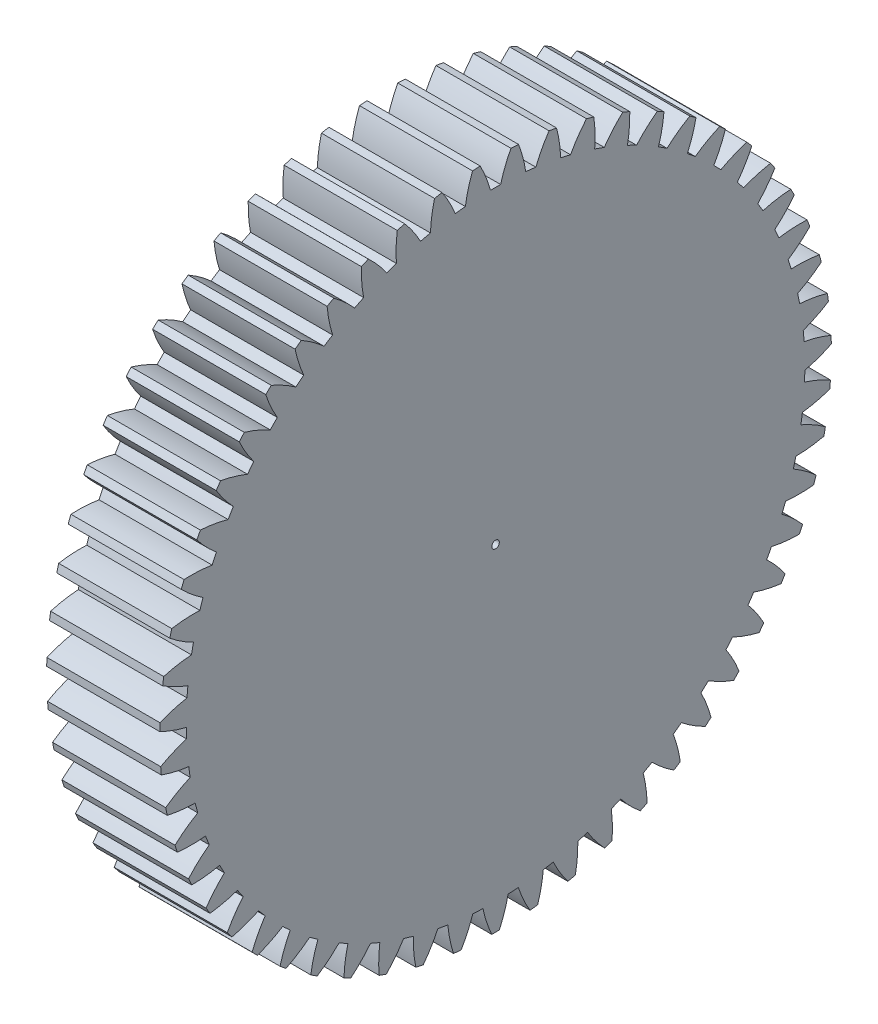
SolidWorks part; units mm, degrees
ref_plane "Plane1" through (0, 0, 0) normal (0, 0, 1) x (1, 0, 0)
ref_plane "Plane2" through (0, 0, 0) normal (0, 1, 0) x (1, 0, 0)
ref_plane "Plane3" through (0, 0, 0) normal (1, 0, 0) x (0, 0, -1)
other "Configuration Table"
sketch "HoldingSke" plane through (0, 0, 0) normal (0, 1, 0) x (1, 0, 0)
  line L0 (0, 0) -> (0.4589, -0.6553)
  line L1 (-15, 0) -> (100, 0) construction
  line L2 (0, 0) -> (-2.1039, 2.3779)
  line L3 (0, 0) -> (-11.863, 4.5341)
  line L4 (0, 0) -> (4.9534, 7.0742)
  line L5 (0, 0) -> (-46.8476, -17.4728)
  line L6 (0, 0) -> (-9.9476, -6.7116)
  line L7 (-2.1039, 2.3779) -> (8.6586, 51.2059)
  line L8 (-76.2, 54.61) -> (-76.1, 54.61)
  line L9 (-71.009, 38.7566) -> (-53.1078, 45.2721)
  line L10 (-76.2, 71.12) -> (104.1128, 71.12)
  line L11 (0, 0) -> (-12, 0)
  line L12 (-76.2, 101.6) -> (-76.155, 101.6)
  line L13 (24.9733, 27.94) -> (52.9518, 28.4284)
  line L14 (24.9733, 27.94) -> (24.9743, 27.94)
  line L15 (24.9733, 27.94) -> (100.4006, 29.5858)
  line L16 (-63.627, -1.25) -> (-12.827, -1.25)
  circle A0 centre (0, 0) radius 0.4
  circle A1 centre (0, 0) radius 32.8115
  circle A2 centre (0, 0) radius 37.5
  circle A3 centre (0, 0) radius 0.4
  dimension "MHD" = 65.623
  dimension "Hub_dia" = 75
  dimension "Bore" = 0.8
  dimension "MBD" = 0.8
  dimension "Num_teeth" = 55
  dimension "Pitch" = 0.8
  dimension "Overall_len" = 50
  dimension "Show_teeth" = 55
  dimension "Thickness" = 12
  dimension "OAL" = 50.0001
  dimension "T_dim" = 0.1
  dimension "Ap" = 20
  dimension "H" = 19.05
  dimension "Pitch_radius" = 180.3128
  dimension "Width" = 12
  dimension "Backlash" = 0.045
  dimension "Addendum_fac" = 1
  dimension "Dedendum_fac" = 1.25
  dimension "Clearance_fac" = 0.25
  dimension "Dedendum_add" = 0.001
  dimension "Module" = 1.25
sketch "BasProSke" plane through (0, 0, 0) normal (0, 1, 0) x (1, 0, 0)
  line L0 (-10, 0) -> (60, 0) construction
  line L1 (0, 0) -> (0, 35.625)
  line L2 (0, 0) -> (12, 0)
  line L3 (12, 0) -> (12, 35.625)
  line L4 (12, 35.625) -> (0, 35.625)
  dimension "Thickness" = 12
  dimension "Diameter" = 71.25
revolve "Base-Revolve" add sketch "BasProSke" angle 360 about L0
sketch "TooCutSke" plane through (0, 0, 0) normal (1, 0, 0) x (0, 0, -1)
  line L1 (0, 0) -> (0, 107) construction
  line L2 (0, 0) -> (-1.0604, 34.3586) construction
  line L3 (0, 0) -> (-3.9235, 68.6142) construction
  line L4 (-1.0604, 34.3586) -> (-1.9618, 34.3071) construction
  arc A0 (0.5379, 32.8071) -> (-0.5379, 32.8071) centre (0, 0) ccw
  arc A1 (1.6425, 35.6125) -> (-1.6425, 35.6125) centre (0, 0) ccw
  circle A2 centre (0, 0) radius 34.375 construction
  circle A3 centre (0, 0) radius 32.3019 construction
  arc A4 (-0.5379, 32.8071) -> (-1.6425, 35.6125) centre (-13.807, 29.2024) ccw
  arc A5 (1.6425, 35.6125) -> (0.5379, 32.8071) centre (13.807, 29.2024) ccw
  dimension "Root_dia" = 65.623
  dimension "Overcut_dia" = 71.3008
  dimension "Pitch_dia" = 68.75
  dimension "Base_dia" = 64.6039
  dimension "Flank_rad" = 13.75
  dimension "Half_ang" = 3.273
  dimension "Half_CT" = 0.9029
extrude "ToothCut" cut sketch "TooCutSke" along normal through all
fillet "Breaks" [suppressed] radius 0.025
fillet "RootFillets" [suppressed] radius 0.3135
pattern_circular "TeethCuts" count 55 every 6.545 about axis through (-10, 0, 0) along (1, 0, 0) of "ToothCut", "RootFillets", "Breaks"
sketch "HubNeaOneSke" plane through (0, 0, 0) normal (-1, 0, 0) x (0, 0, 1)
  circle A0 centre (0, 0) radius 32.8115
  dimension "Diameter" = 65.623
extrude "HubNearOne" [suppressed] add sketch "HubNeaOneSke" along normal blind 38.0001
sketch "HubNeaBotSke" plane through (0, 0, 0) normal (-1, 0, 0) x (0, 0, 1)
  circle A0 centre (0, 0) radius 32.8115
  dimension "Diameter" = 65.623
extrude "HubNearBoth" [suppressed] add sketch "HubNeaBotSke" along normal blind 19
ref_plane "FarPln" through (12, 0, 0) normal (1, 0, 0) x (0, 0, -1)
sketch "HubFarSke" plane through (12, 0, 0) normal (1, 0, 0) x (0, 0, -1)
  circle A0 centre (0, 0) radius 32.8115
  dimension "Diameter" = 65.623
extrude "HubFar" [suppressed] add sketch "HubFarSke" along normal blind 19
sketch "BorSke" plane through (0, 0, 0) normal (1, 0, 0) x (0, 0, -1)
  circle A0 centre (0, 0) radius 0.4
  dimension "Diameter" = 0.8
extrude "Bore" cut sketch "BorSke" along normal mid plane 100.0001
sketch "KeySke" plane through (0, 0, 0) normal (1, 0, 0) x (0, 0, -1)
  line L0 (-0.05, 0) -> (-0.05, 0.5)
  line L1 (-0.05, 0.5) -> (0.05, 0.5)
  line L2 (0.05, 0.5) -> (0.05, 0)
  line L3 (0, 0) -> (0, 34) construction
  line L4 (-0.05, 0) -> (0.05, 0)
  dimension "Offset" = 0.5
  dimension "Width" = 0.1
extrude "Keyway" [suppressed] cut sketch "KeySke" along normal mid plane 100.0001
pattern_circular "Keyway2" [suppressed] count 2 every 90 about axis through (-10, 0, 0) along (1, 0, 0)
equation "' \"Module@HoldingSke\" = 6.35"
equation "' \"Num_teeth@HoldingSke\" = 12"
equation "' \"Ap@HoldingSke\" =  20"
equation "' \"Ap@HoldingSke\" = 20"
equation "' \"Width@HoldingSke\" = 0.5 * 25.4"
equation "' \"Hub_dia@HoldingSke\"= 1 * 25.4"
equation "' \"Hub_dia@HoldingSke\" = 1 * 25.4"
equation "' \"Overall_len@HoldingSke\" = 1.0 * 25.4"
equation "' \"Bore@HoldingSke\" = 0.75 * 25.4"
equation "' \"T_dim@HoldingSke\" = 0.1 * 25.4"
equation "' \"Width@KeySke\" = 0.25 * 25.4"
equation "' \"Show_teeth@HoldingSke\" = 13"
equation "' \"Backlash@HoldingSke\" = 0.009 * 25.4"
equation "' \"Addendum_fac@HoldingSke\" = 1.0"
equation "' \"Dedendum_fac@HoldingSke\" = 1.25"
equation "' \"Dedendum_add@HoldingSke\" = 0.00005 * 25.4"
equation "' \"Clearance_fac@HoldingSke\" = 0.25"
equation "\"Pitch@HoldingSke\" = 1 / \"Module@HoldingSke\""
equation "\"Overcut_dia@TooCutSke\" = (\"Num_teeth@HoldingSke\" + 2 * \"Addendum_fac@HoldingSke\") / \"Pitch@HoldingSke\" + 0.002 * 25.4"
equation "\"Pitch_dia@TooCutSke\" = \"Num_teeth@HoldingSke\" / \"Pitch@HoldingSke\""
equation "\"Base_dia@TooCutSke\" = \"Num_teeth@HoldingSke\" / \"Pitch@HoldingSke\" * cos((\"Ap@HoldingSke\"  * 3.14159265 / 180))"
equation "\"Root_dia@TooCutSke\" = (\"Num_teeth@HoldingSke\" + 2) / \"Pitch@HoldingSke\" - 2 * (\"Addendum_fac@HoldingSke\" + \"Dedendum_fac@HoldingSke\") / \"Pitch@HoldingSke\" - \"Dedendum_add@HoldingSke\" * 2"
equation "\"Half_ang@TooCutSke\" = 180 / \"Num_teeth@HoldingSke\""
equation "\"Half_CT@TooCutSke\" = \"Num_teeth@HoldingSke\" / \"Pitch@HoldingSke\" * sin((3.14159265 / 2 / \"Num_teeth@HoldingSke\")) / 2 - 7 * \"Backlash@HoldingSke\" / 4"
equation "\"Flank_rad@TooCutSke\" = \"Num_teeth@HoldingSke\" / \"Pitch@HoldingSke\" / 5"
equation "\"Radius@RootFillets\" = \"Clearance_fac@HoldingSke\" / \"Pitch@HoldingSke\" + \"Dedendum_add@HoldingSke\""
equation "\"Break_rad@Breaks\" = 0.02 / \"Pitch@HoldingSke\""
equation "\"Thickness@HoldingSke\" = \"Width@HoldingSke\""
equation "\"OAL@HoldingSke\" = \"Thickness@HoldingSke\""
equation "\"MHD@HoldingSke\" = (\"Num_teeth@HoldingSke\" + 2) / \"Pitch@HoldingSke\" - 2 * (\"Addendum_fac@HoldingSke\" + \"Dedendum_fac@HoldingSke\")  / \"Pitch@HoldingSke\" - \"Dedendum_add@HoldingSke\" * 2"
equation "\"MBD@HoldingSke\" = (\"Num_teeth@HoldingSke\" + 2) / \"Pitch@HoldingSke\" - 2 * (\"Addendum_fac@HoldingSke\" + \"Dedendum_fac@HoldingSke\")  / \"Pitch@HoldingSke\" - \"Dedendum_add@HoldingSke\" * 2 - 0.002 * 25.4"
equation "\"MHD@HoldingSke\" = ((sgn( \"MHD@HoldingSke\" - \"Hub_dia@HoldingSke\" )-1)*( \"MHD@HoldingSke\" - \"Hub_dia@HoldingSke\" ))/-2+ \"Hub_dia@HoldingSke\""
equation "\"MBD@HoldingSke\" = ((sgn( \"MBD@HoldingSke\" - \"Bore@HoldingSke\" )-1)*( \"MBD@HoldingSke\" - \"Bore@HoldingSke\" ))/-2+ \"Bore@HoldingSke\""
equation "\"OAL@HoldingSke\" = ((sgn( \"OAL@HoldingSke\" - \"Overall_len@HoldingSke\" )+1)*( \"OAL@HoldingSke\" - \"Overall_len@HoldingSke\" ))/2 + \"Overall_len@HoldingSke\" + 0.000002 * 25.4"
equation "\"Num_teeth@TeethCuts\" = int( \"Show_teeth@HoldingSke\" ) + 1"
equation "\"Num_teeth@TeethCuts\" = ((sgn( \"Num_teeth@TeethCuts\" - \"Num_teeth@HoldingSke\" )-1)*( \"Num_teeth@TeethCuts\" - \"Num_teeth@HoldingSke\" ))/-2+ \"Num_teeth@HoldingSke\""
equation "\"Num_teeth@TeethCuts\" = ((sgn( \"Num_teeth@TeethCuts\" - 2.0)+1)*( \"Num_teeth@TeethCuts\" - 2.0))/2 +2.0"
equation "\"Angle@TeethCuts\" = 360.0 / \"Num_teeth@HoldingSke\""
equation "\"Diameter@BasProSke\" = (\"Num_teeth@HoldingSke\" + 2 * \"Addendum_fac@HoldingSke\") / \"Pitch@HoldingSke\""
equation "\"Thickness@BasProSke\"  = \"Thickness@HoldingSke\""
equation "' \"Fillet_rad@BasProSke\" =  \"Thickness@HoldingSke\" * 0.05"
equation "' \"Fillet_rad@BasProSke\" = \"Thickness@HoldingSke\" * 0.05"
equation "\"MHD@HoldingSke\" = ((sgn( \"MHD@HoldingSke\" - \"Root_dia@TooCutSke\" )-1)*( \"MHD@HoldingSke\" - \"Root_dia@TooCutSke\" ))/-2+ \"Root_dia@TooCutSke\""
equation "\"Diameter@HubNeaOneSke\" = \"MHD@HoldingSke\""
equation "\"Length@HubNearOne\" = \"OAL@HoldingSke\" - \"Thickness@BasProSke\""
equation "\"Diameter@HubNeaBotSke\" = \"MHD@HoldingSke\""
equation "\"Length@HubNearBoth\" = ( \"OAL@HoldingSke\" - \"Thickness@BasProSke\" ) / 2.0"
equation "\"Thickness@FarPln\" = \"Thickness@BasProSke\""
equation "\"Diameter@HubFarSke\" = \"MHD@HoldingSke\""
equation "\"Length@HubFar\" = ( \"OAL@HoldingSke\" - \"Thickness@BasProSke\" ) / 2.0"
equation "\"Diameter@BorSke\" = \"MBD@HoldingSke\""
equation "\"D1@Bore\" = \"OAL@HoldingSke\" * 2.0"
equation "\"D1@Keyway\" = \"OAL@HoldingSke\" * 2.0"
equation "\"Offset@KeySke\" = \"T_dim@HoldingSke\" + \"MBD@HoldingSke\" / 2.0"
